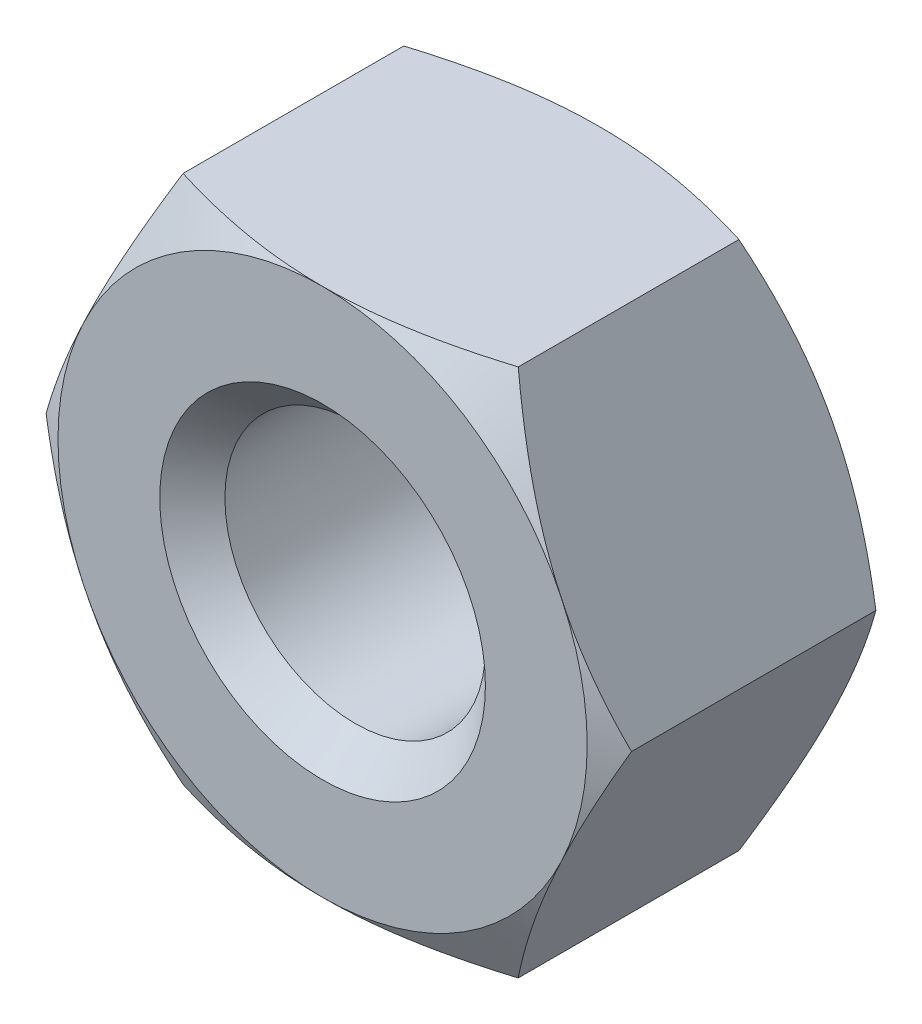
SolidWorks part; units mm, degrees
extrude "Base-Extrusion" add sketch "Esquisse1" along normal blind 6.8
sketch "Esquisse1" plane through (0, 0, 0) normal (0, 0, 1) x (1, 0, 0)
  line L0 (-7.19, 0) -> (-4.1165, 6.5)
  line L1 (-4.1165, 6.5) -> (4.1165, 6.5)
  line L2 (4.1165, 6.5) -> (7.19, 0)
  line L3 (7.19, 0) -> (4.1165, -6.5)
  line L4 (4.1165, -6.5) -> (-4.1165, -6.5)
  line L5 (-4.1165, -6.5) -> (-7.19, 0)
  dimension "D1" = 6.5
  dimension "D2" = 13
  dimension "D3" = 6.5
  dimension "D4" = 13
  dimension "D5" = 14.38
revolve "Enlever de la matière-Révolution1" cut sketch "Esquisse3" angle 360 about L7
sketch "Esquisse3" plane through (0, 0, 0) normal (1, 0, 0) x (0, 0, -1)
  line L0 (-6.8, 6.5) -> (-3.4, 12.389)
  line L1 (-3.4, 12.389) -> (0, 6.5)
  line L2 (0, 6.5) -> (2.5981, 8)
  line L3 (2.5981, 8) -> (-3.4, 18.389)
  line L4 (-6.8, 6.5) -> (-9.3981, 8)
  line L5 (-9.3981, 8) -> (-3.4, 18.389)
  line L6 (-6.8, 6.5) -> (0, 6.5) construction
  line L7 (-8.496, 0) -> (1.9245, 0) construction
  dimension "D1" = 60
  dimension "D2" = 3
ref_plane "Plan1" through (0, 0, 0) normal (0, 0, 1) x (1, 0, 0)
ref_plane "Plan2" through (0, 0, 0) normal (0, 1, 0) x (1, 0, 0)
ref_plane "Plan3" through (0, 0, 0) normal (1, 0, 0) x (0, 0, -1)
sketch "Esquisse4" plane through (0, 0, 6.8) normal (0, 0, 1) x (1, 0, 0)
  circle A0 centre (0, 0) radius 3.2
  dimension "D1" = 6.4
extrude "Enlèv. mat.-Extru.1" cut sketch "Esquisse4" against normal through all
chamfer "Chanfrein1" distance 0.8 angle 45
